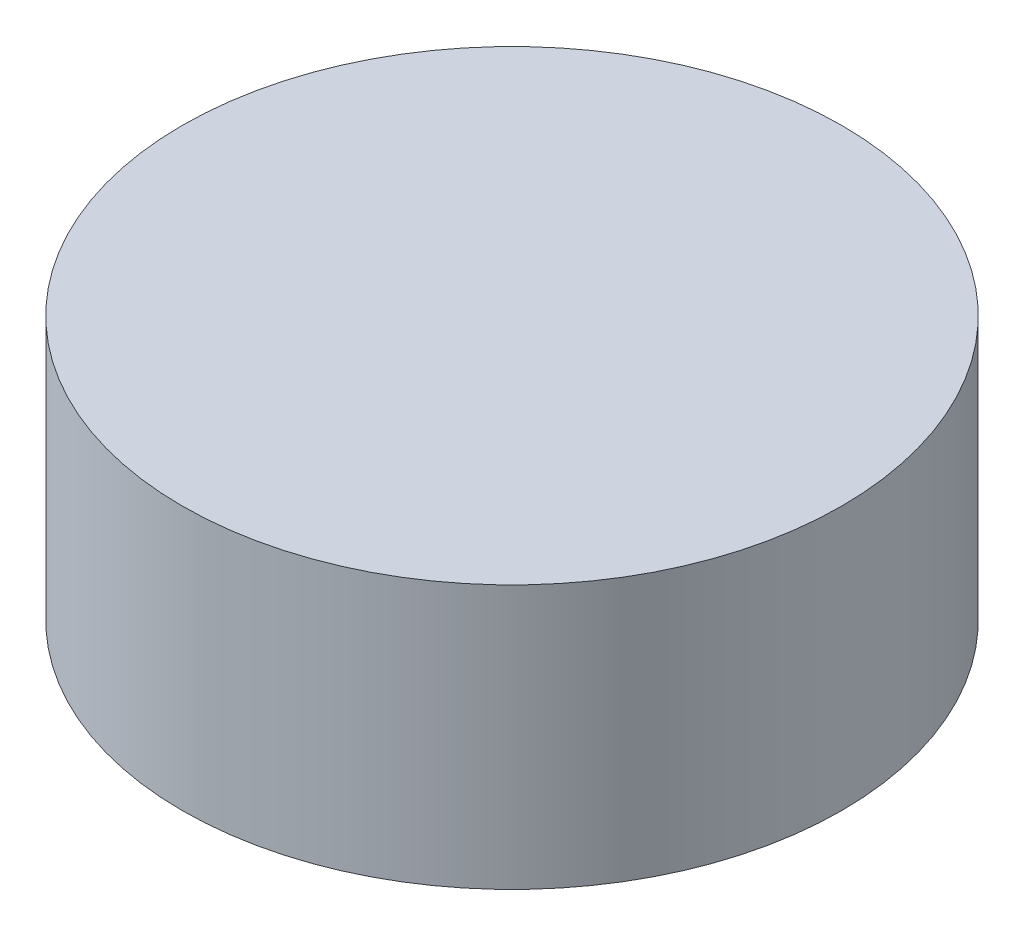
SolidWorks part; units mm, degrees
ref_plane "Front Plane" through (0, 0, 0) normal (0, 0, 1) x (1, 0, 0)
ref_plane "Top Plane" through (0, 0, 0) normal (0, 1, 0) x (1, 0, 0)
ref_plane "Right Plane" through (0, 0, 0) normal (1, 0, 0) x (0, 0, -1)
sketch "Sketch1" plane through (0, 0, 0) normal (0, 1, 0) x (1, 0, 0)
  circle A0 centre (0, 0) radius 6.35
  dimension "D1" = 12.7
extrude "Boss-Extrude1" add sketch "Sketch1" along normal blind 5.08
